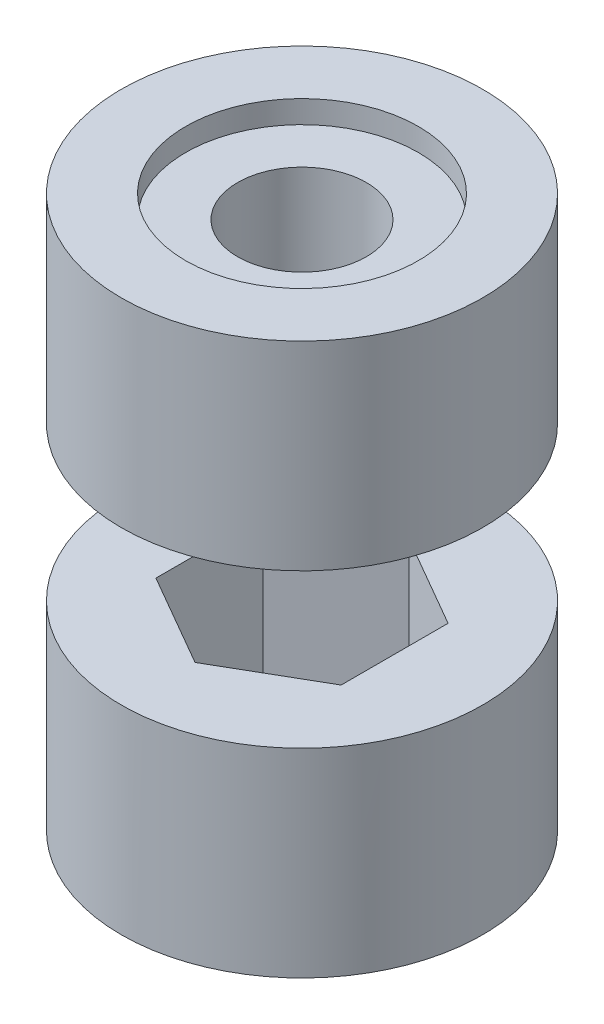
SolidWorks part; units mm, degrees
ref_plane "Front Plane" through (0, 0, 0) normal (0, 0, 1) x (1, 0, 0)
ref_plane "Top Plane" through (0, 0, 0) normal (0, 1, 0) x (1, 0, 0)
ref_plane "Right Plane" through (0, 0, 0) normal (1, 0, 0) x (0, 0, -1)
sketch "Sketch1" plane through (0, 0, 0) normal (0, 1, 0) x (1, 0, 0)
  circle A0 centre (0, 0) radius 8
extrude "Boss-Extrude1" add sketch "Sketch1" along normal blind 24.418
sketch "Sketch2" plane through (0, 0, 0) normal (0, 0, 1) x (1, 0, 0)
  line L0 (-10.2, 8.809) -> (10.2, 8.809)
  line L1 (10.2, 8.809) -> (10.2, 15.609)
  line L2 (10.2, 15.609) -> (-10.2, 15.609)
  line L3 (-10.2, 15.609) -> (-10.2, 8.809)
extrude "Cut-Extrude1" cut sketch "Sketch2" against normal through all and the other way through all
sketch "Sketch3" plane through (0, 0, 0) normal (0, 1, 0) x (1, 0, 0)
  circle A0 centre (0, 0) radius 2.85
extrude "Cut-Extrude2" cut sketch "Sketch3" along normal blind 24.418
ref_plane "Plane1" through (0, 24.418, 0) normal (0, 1, 0) x (1, 0, 0)
sketch "Sketch4" plane through (0, 24.418, 0) normal (0, 1, 0) x (1, 0, 0)
  circle A0 centre (0, 0) radius 5.15
extrude "Cut-Extrude3" cut sketch "Sketch4" against normal blind 1
sketch "Sketch5" plane through (0, 0, 0) normal (0, 1, 0) x (1, 0, 0)
  line L0 (4.1, -2.3671) -> (0, -4.7343)
  line L1 (0, -4.7343) -> (-4.1, -2.3671)
  line L2 (-4.1, -2.3671) -> (-4.1, 2.3671)
  line L3 (-4.1, 2.3671) -> (0, 4.7343)
  line L4 (0, 4.7343) -> (4.1, 2.3671)
  line L5 (4.1, 2.3671) -> (4.1, -2.3671)
extrude "Cut-Extrude4" cut sketch "Sketch5" along normal blind 9
